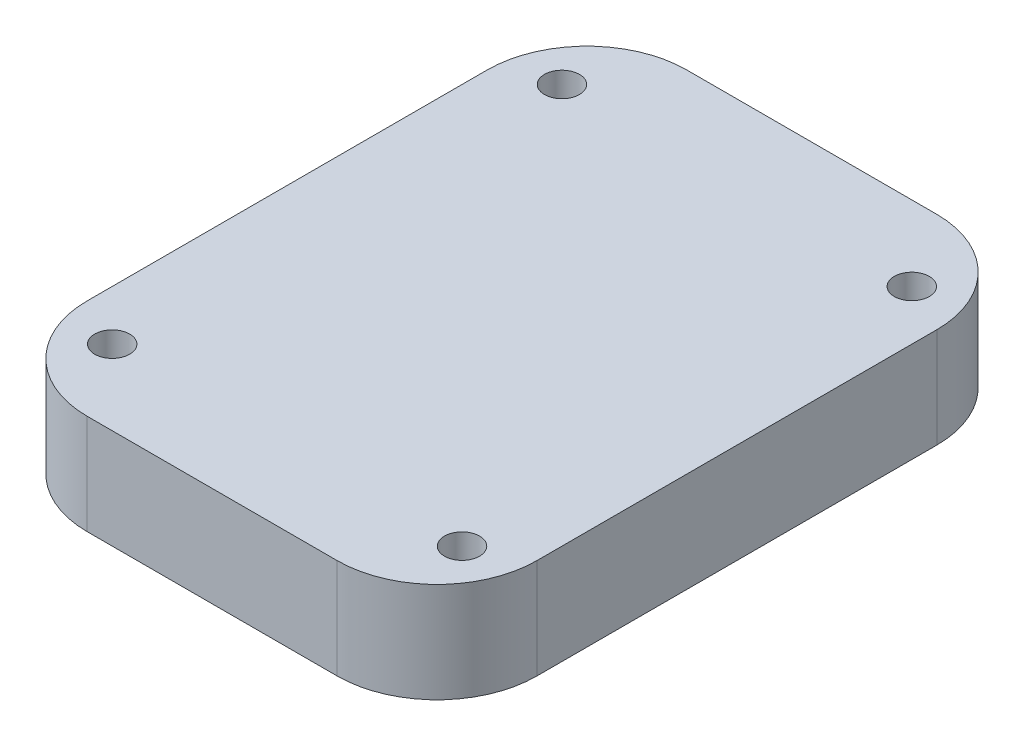
SolidWorks part; units mm, degrees
ref_plane "Plan de face" through (0, 0, 0) normal (0, 0, 1) x (1, 0, 0)
ref_plane "Plan de dessus" through (0, 0, 0) normal (0, 1, 0) x (1, 0, 0)
ref_plane "Plan de droite" through (0, 0, 0) normal (1, 0, 0) x (0, 0, -1)
sketch "Esquisse2" plane through (0, 0, 0) normal (0, 1, 0) x (1, 0, 0)
  line L1 (-12.5, 30) -> (12.5, 30)
  line L2 (-22.5, 20) -> (-22.5, -20)
  line L3 (-12.5, -30) -> (12.5, -30)
  line L4 (22.5, 20) -> (22.5, -20)
  arc A0 (12.5, 30) -> (22.5, 20) centre (12.5, 20) cw
  arc A1 (12.5, -30) -> (22.5, -20) centre (12.5, -20) ccw
  arc A2 (-22.5, -20) -> (-12.5, -30) centre (-12.5, -20) ccw
  arc A3 (-12.5, 30) -> (-22.5, 20) centre (-12.5, 20) ccw
  point P4 (-22.5, 0)
  point P6 (0, 30)
  point P9 (22.5, 30)
  point P14 (-22.5, -30)
  point P17 (-22.5, 30)
  dimension "D3" = 10
  dimension "D1" = 45
  dimension "D2" = 60
extrude "Boss.-Extru.1" add sketch "Esquisse2" along normal blind 10 contours L2 A2 L3 A1 L4 A0 L1 A3
sketch "Sketch1" plane through (0, 10, 0) normal (0, 1, 0) x (1, 0, 0)
  line L0 (-17.5, 22.5) -> (-17.5, -22.5) construction
  line L1 (-17.5, 22.5) -> (17.5, 22.5) construction
  circle A0 centre (-17.5, 22.5) radius 1.75
  circle A1 centre (17.5, 22.5) radius 1.75
  circle A2 centre (17.5, -22.5) radius 1.75
  circle A3 centre (-17.5, -22.5) radius 1.75
  point P8 (-17.5, 0)
  point P9 (0, 22.5)
  point P11 (0, 0)
  point P12 (0, 0)
  point P13 (0, 0)
  point P14 (0, 0)
  dimension "D1" = 3.5
  dimension "D2" = 3.5
  dimension "D3" = 3.5
  dimension "D4" = 3.5
  dimension "D5" = 45
  dimension "D6" = 35
extrude "Cut-Extrude1" cut sketch "Sketch1" against normal through all
